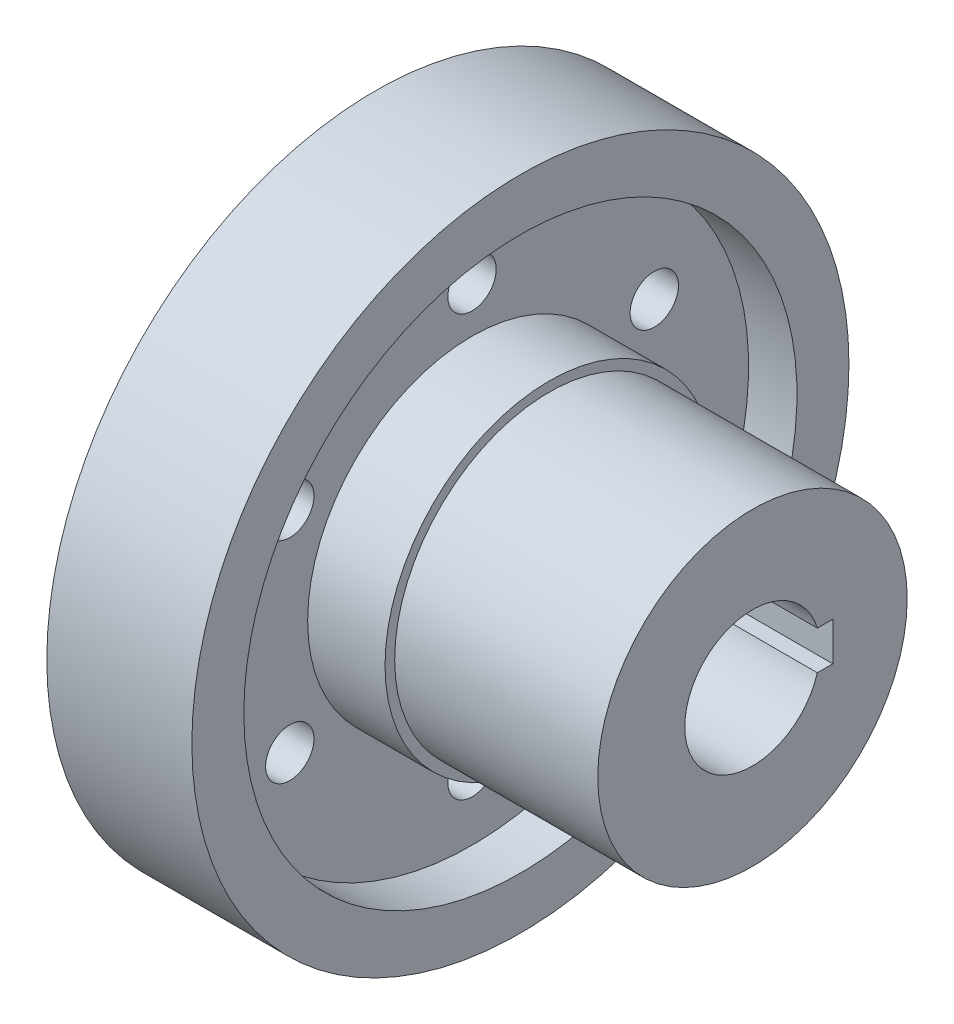
SolidWorks part; units mm, degrees
ref_plane "Front Plane" through (0, 0, 0) normal (0, 0, 1) x (1, 0, 0)
ref_plane "Top Plane" through (0, 0, 0) normal (0, 1, 0) x (1, 0, 0)
ref_plane "Right Plane" through (0, 0, 0) normal (1, 0, 0) x (0, 0, -1)
sketch "Sketch1" plane through (0, 0, 0) normal (0, 1, 0) x (1, 0, 0)
  line L0 (-159.75, 0) -> (152.8043, 0) construction
  line L1 (-13.7717, 35) -> (128.2283, 35)
  line L2 (128.2283, 35) -> (128.2283, 80)
  line L3 (128.2283, 80) -> (23.2283, 80)
  line L4 (23.2283, 80) -> (23.2283, 85)
  line L5 (23.2283, 85) -> (-16.7717, 85)
  line L6 (-16.7717, 85) -> (-16.7717, 143)
  line L7 (-16.7717, 143) -> (8.2283, 143)
  line L8 (8.2283, 143) -> (8.2283, 169.875)
  line L9 (8.2283, 169.875) -> (-66.7717, 169.875)
  line L10 (-66.7717, 169.875) -> (-66.7717, 90)
  line L11 (-66.7717, 90) -> (-71.7717, 90)
  line L12 (-71.7717, 90) -> (-71.7717, 60)
  line L13 (-71.7717, 60) -> (-13.7717, 60)
  line L14 (-13.7717, 60) -> (-13.7717, 35)
  dimension "D1" = 142
  dimension "D2" = 105
  dimension "D3" = 45
  dimension "D4" = 5
  dimension "D5" = 58
  dimension "D6" = 25
  dimension "D7" = 30
  dimension "D8" = 5
  dimension "D9" = 25
  dimension "D10" = 75
  dimension "D11" = 58
  dimension "D12" = 35
revolve "Revolve1" add sketch "Sketch1" angle 360 about L0
sketch "Sketch2" plane through (128.2283, 0, 0) normal (1, 0, 0) x (0, 0, -1)
  line L1 (33.541, 10) -> (41.541, 10)
  line L2 (33.541, 10) -> (33.541, -10)
  line L3 (33.541, -10) -> (41.541, -10)
  line L4 (41.541, 10) -> (41.541, -10)
  circle A0 centre (0, 0) radius 35 construction
  point P6 (0, 0)
  dimension "D1" = 8
  dimension "D2" = 8
  dimension "D3" = 20
extrude "Cut-Extrude1" cut sketch "Sketch2" against normal through all
sketch "Sketch3" plane through (-16.7717, 0, 0) normal (1, 0, 0) x (0, 0, -1)
  line L0 (0, 121.5523) -> (0, -111.992) construction
  circle A0 centre (0, 108.8053) radius 12.5
  circle A1 centre (94.2281, 54.4026) radius 12.5
  circle A2 centre (94.2281, -54.4026) radius 12.5
  circle A3 centre (0, -108.8053) radius 12.5
  circle A4 centre (-94.2281, -54.4026) radius 12.5
  circle A5 centre (-94.2281, 54.4026) radius 12.5
  point P17 (0, 0)
  dimension "D1" = 25
  dimension "D2" = 6
extrude "Cut-Extrude2" cut sketch "Sketch3" against normal through all
